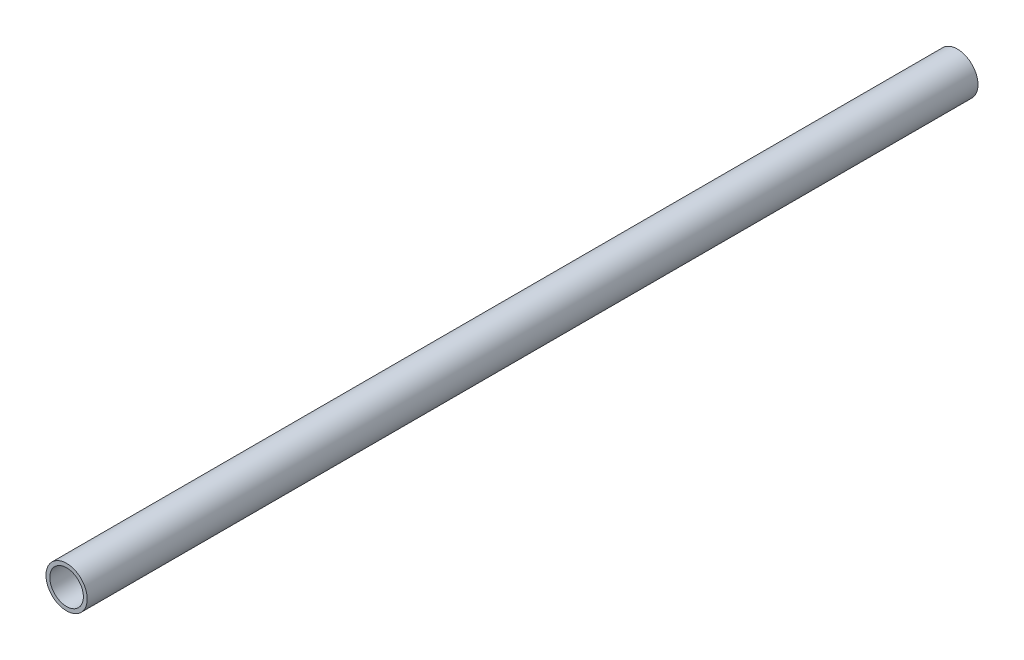
SolidWorks part; units mm, degrees
ref_plane "Alzado" through (0, 0, 0) normal (0, 0, 1) x (1, 0, 0)
ref_plane "Planta" through (0, 0, 0) normal (0, 1, 0) x (1, 0, 0)
ref_plane "Vista lateral" through (0, 0, 0) normal (1, 0, 0) x (0, 0, -1)
sketch "Croquis1" plane through (0, 0, 0) normal (0, 0, 1) x (1, 0, 0)
  circle A0 centre (0, 0) radius 6.6
  circle A1 centre (0, 0) radius 8.1
  dimension "D1" = 16.2
  dimension "D2" = 1.5
extrude "Saliente-Extruir1" add sketch "Croquis1" along normal mid plane 350
